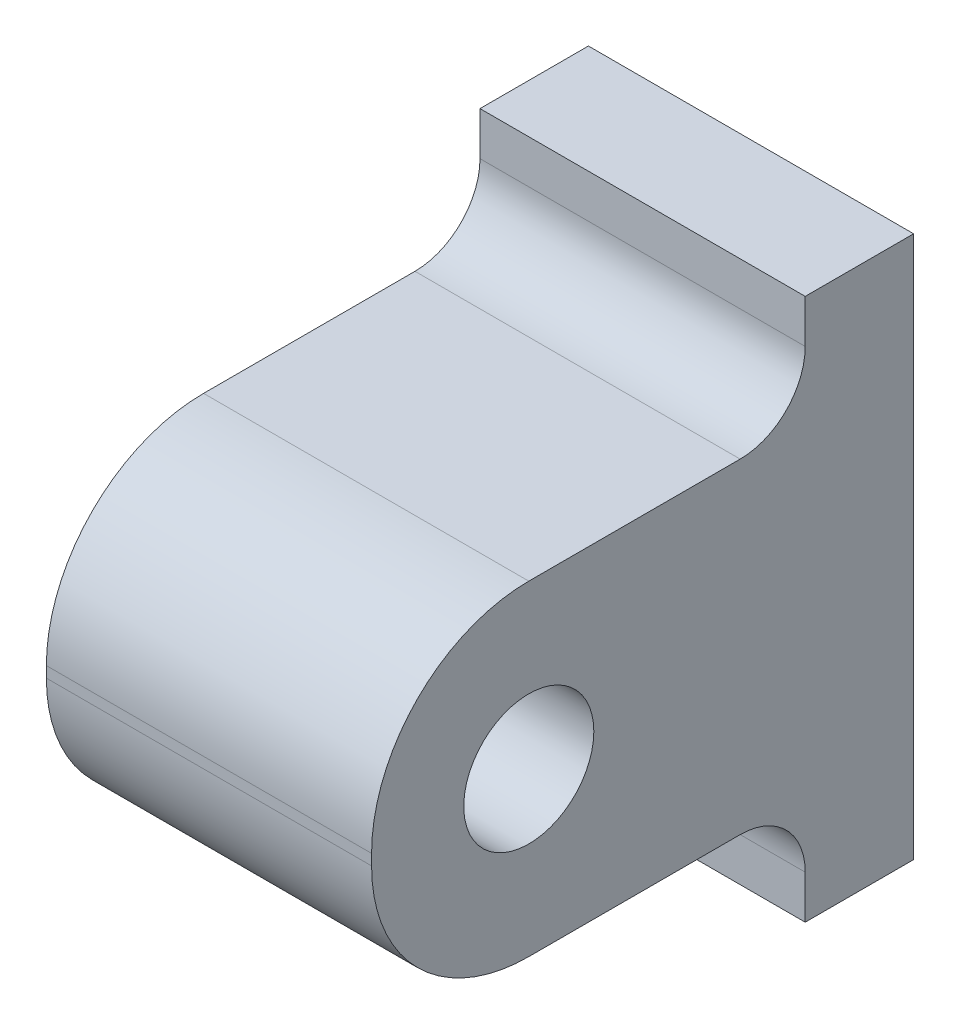
SolidWorks part; units mm, degrees
ref_plane "Plano frontal" through (0, 0, 0) normal (0, 0, 1) x (1, 0, 0)
ref_plane "Plano superior" through (0, 0, 0) normal (0, 1, 0) x (1, 0, 0)
ref_plane "Plano direito" through (0, 0, 0) normal (1, 0, 0) x (0, 0, -1)
sketch "Esboço1" plane through (0, 0, 0) normal (1, 0, 0) x (0, 0, -1)
  line L0 (29.0812, 22.4139) -> (29.0812, -27.5861)
  line L1 (29.0812, -27.5861) -> (19.0812, -27.5861)
  line L2 (19.0812, -27.5861) -> (19.0812, -23.5861)
  line L3 (13.0812, -17.5861) -> (-6.4188, -17.5861)
  line L4 (29.0812, 22.4139) -> (19.0812, 22.4139)
  line L5 (19.0812, 22.4139) -> (19.0812, 18.4139)
  line L6 (13.0812, 12.4139) -> (-6.4188, 12.4139)
  line L7 (-20.9188, -2.0861) -> (-20.9188, -3.0861)
  arc A0 (19.0812, -23.5861) -> (13.0812, -17.5861) centre (13.0812, -23.5861) ccw
  arc A1 (13.0812, 12.4139) -> (19.0812, 18.4139) centre (13.0812, 18.4139) ccw
  arc A2 (-6.4188, -17.5861) -> (-20.9188, -3.0861) centre (-6.4188, -3.0861) cw
  arc A3 (-6.4188, 12.4139) -> (-20.9188, -2.0861) centre (-6.4188, -2.0861) ccw
extrude "Ressalto-extrusão1" add sketch "Esboço1" along normal blind 30
sketch "Esboço2" plane through (0, 0, 0) normal (1, 0, 0) x (0, 0, -1)
  circle A0 centre (-6.4188, -2.5861) radius 6
extrude "Corte-extrusão1" cut sketch "Esboço2" along normal blind 30 contours A0
